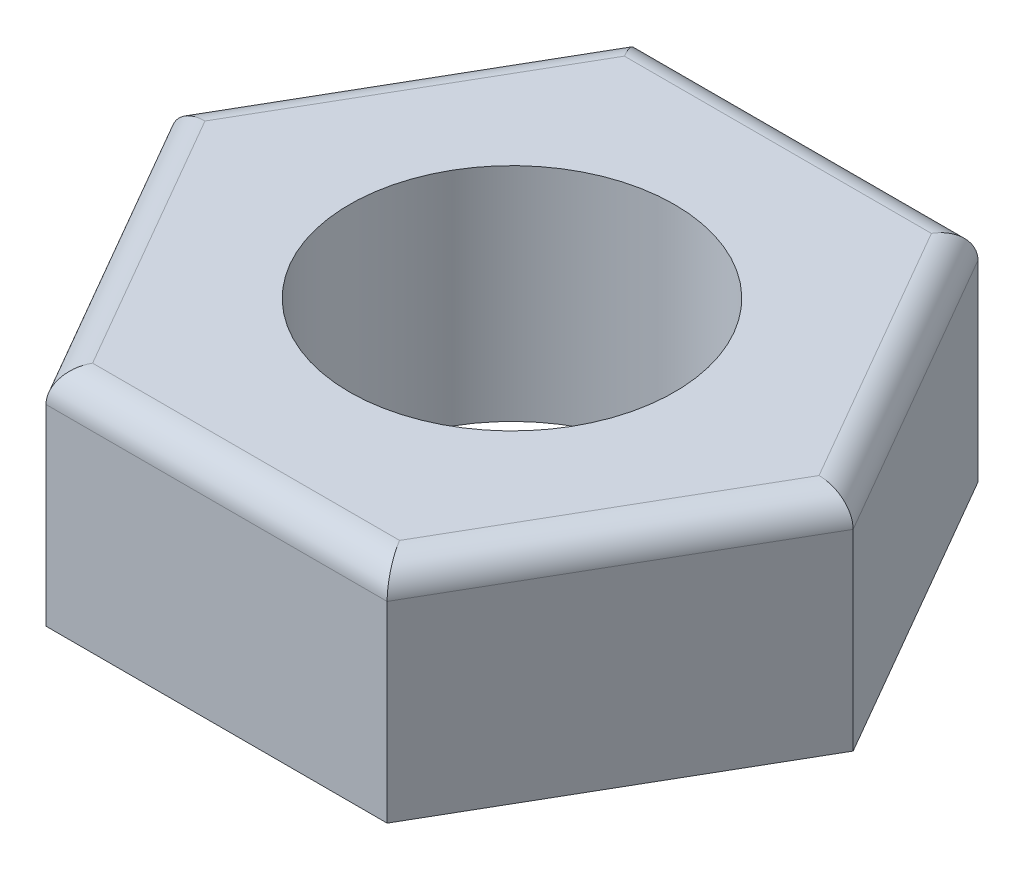
SolidWorks part; units mm, degrees
ref_plane "前视基准面" through (0, 0, 0) normal (0, 0, 1) x (1, 0, 0)
ref_plane "上视基准面" through (0, 0, 0) normal (0, 1, 0) x (1, 0, 0)
ref_plane "右视基准面" through (0, 0, 0) normal (1, 0, 0) x (0, 0, -1)
sketch "草图1" plane through (0, 0, 0) normal (0, 1, 0) x (1, 0, 0)
  line L1 (-11.547, -20) -> (11.547, -20)
  line L2 (11.547, -20) -> (23.094, 0)
  line L3 (23.094, 0) -> (11.547, 20)
  line L4 (11.547, 20) -> (-11.547, 20)
  line L5 (-11.547, 20) -> (-23.094, 0)
  line L6 (-23.094, 0) -> (-11.547, -20)
  dimension "D1" = 40
extrude "凸台-拉伸1" add sketch "草图1" along normal blind 15
sketch "草图2" plane through (0, 15, 0) normal (0, 1, 0) x (1, 0, 0)
  circle A0 centre (0, 0) radius 11
  dimension "D1" = 22
extrude "切除-拉伸1" cut sketch "草图2" against normal through all
fillet "圆角1" radius 2 6 edges at (0, 15, 20) (-17.3205, 15, 10) (-17.3205, 15, -10) (0, 15, -20) (17.3205, 15, -10) (17.3205, 15, 10)
